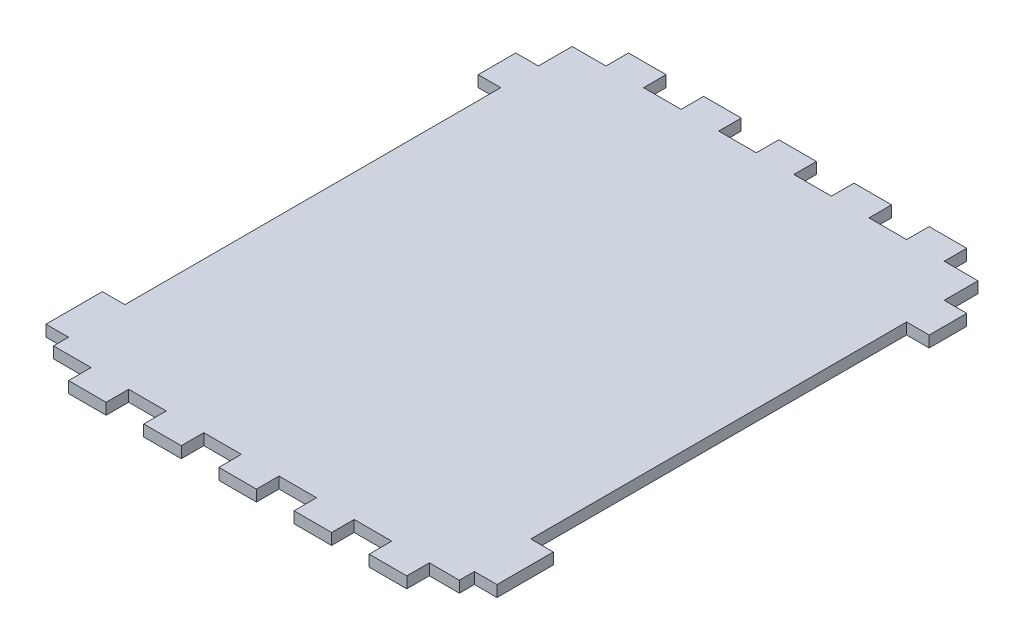
SolidWorks part; units mm, degrees
ref_plane "Спереди" through (0, 0, 0) normal (0, 0, 1) x (1, 0, 0)
ref_plane "Сверху" through (0, 0, 0) normal (0, 1, 0) x (1, 0, 0)
ref_plane "Справа" through (0, 0, 0) normal (1, 0, 0) x (0, 0, -1)
other "Configuration Table"
sketch "Эскиз1" plane through (0, 0, 0) normal (0, 1, 0) x (1, 0, 0)
  line L1 (0, 0) -> (108, 0)
  line L2 (0, 0) -> (0, -138)
  line L3 (0, -138) -> (108, -138)
  line L4 (108, 0) -> (108, -138)
  dimension "D1" = 138
  dimension "D2" = 108
extrude "Бобышка-Вытянуть1" add sketch "Эскиз1" along normal blind 4
sketch "Эскиз3" plane through (0, 0, 0) normal (0, -1, 0) x (1, 0, 0)
  line L1 (0, 138) -> (108, 138)
  line L2 (0, 138) -> (0, 0)
  line L3 (0, 0) -> (108, 0)
  line L4 (108, 138) -> (108, 0)
extrude "Вырез-Вытянуть2" cut sketch "Эскиз3" against normal blind 1
sketch "Эскиз4" plane through (0, 0, 138) normal (0, 0, 1) x (1, 0, 0)
  line L0 (0, 4) -> (108, 4) construction
  line L1 (10, 4) -> (20, 4)
  line L2 (10, 4) -> (10, 1)
  line L3 (10, 1) -> (20, 1)
  line L4 (20, 4) -> (20, 1)
  line L5 (108, 1) -> (0, 1) construction
  line L6 (0, 4) -> (0, 1) construction
  line L7 (30, 4) -> (30, 1)
  line L8 (30, 4) -> (40, 4)
  line L9 (40, 4) -> (40, 1)
  line L10 (30, 1) -> (40, 1)
  line L11 (50, 4) -> (50, 1)
  line L12 (50, 4) -> (60, 4)
  line L13 (60, 4) -> (60, 1)
  line L14 (50, 1) -> (60, 1)
  line L15 (70, 4) -> (70, 1)
  line L16 (70, 4) -> (80, 4)
  line L17 (80, 4) -> (80, 1)
  line L18 (70, 1) -> (80, 1)
  line L19 (90, 4) -> (90, 1)
  line L20 (90, 4) -> (100, 4)
  line L21 (100, 4) -> (100, 1)
  line L22 (90, 1) -> (100, 1)
  dimension "D1" = 10
  dimension "D2" = 10
  dimension "D3" = 5
extrude "Бобышка-Вытянуть2" add sketch "Эскиз4" along normal blind 6
sketch "Эскиз5" plane through (0, 0, 0) normal (-1, 0, 0) x (0, 0, 1)
  line L0 (0, 4) -> (138, 4) construction
  line L1 (9, 4) -> (19, 4)
  line L2 (9, 4) -> (9, 1)
  line L3 (9, 1) -> (19, 1)
  line L4 (19, 4) -> (19, 1)
  line L5 (138, 1) -> (0, 1) construction
  line L6 (0, 4) -> (0, 1) construction
  line L7 (119, 4) -> (134, 4)
  line L8 (119, 4) -> (119, 1)
  line L9 (119, 1) -> (134, 1)
  line L10 (134, 4) -> (134, 1)
  line L11 (138, 4) -> (138, 1) construction
  dimension "D1" = 10
  dimension "D2" = 9
  dimension "D3" = 15
  dimension "D4" = 4
extrude "Бобышка-Вытянуть3" add sketch "Эскиз5" along normal blind 6
sketch "Эскиз6" plane through (108, 0, 0) normal (1, 0, 0) x (0, 0, -1)
  line L0 (-138, 4) -> (0, 4) construction
  line L1 (-134, 4) -> (-119, 4)
  line L2 (-134, 4) -> (-134, 1)
  line L3 (-134, 1) -> (-119, 1)
  line L4 (-119, 4) -> (-119, 1)
  line L5 (0, 1) -> (-138, 1) construction
  line L6 (-138, 4) -> (-138, 1) construction
  line L7 (-19, 4) -> (-9, 4)
  line L8 (-19, 4) -> (-19, 1)
  line L9 (-19, 1) -> (-9, 1)
  line L10 (-9, 4) -> (-9, 1)
  line L11 (0, 4) -> (0, 1) construction
  dimension "D1" = 15
  dimension "D2" = 4
  dimension "D3" = 10
  dimension "D4" = 9
extrude "Бобышка-Вытянуть4" add sketch "Эскиз6" along normal blind 6
sketch "Эскиз7" plane through (0, 0, 0) normal (0, 0, -1) x (-1, 0, 0)
  line L0 (-108, 4) -> (0, 4) construction
  line L1 (-99, 4) -> (-89, 4)
  line L2 (-99, 4) -> (-99, 1)
  line L3 (-99, 1) -> (-89, 1)
  line L4 (-89, 4) -> (-89, 1)
  line L5 (0, 1) -> (-108, 1) construction
  line L6 (-79, 4) -> (-79, 1)
  line L7 (-79, 4) -> (-69, 4)
  line L8 (-69, 4) -> (-69, 1)
  line L9 (-79, 1) -> (-69, 1)
  line L10 (-59, 4) -> (-59, 1)
  line L11 (-59, 4) -> (-49, 4)
  line L12 (-49, 4) -> (-49, 1)
  line L13 (-59, 1) -> (-49, 1)
  line L14 (-39, 4) -> (-39, 1)
  line L15 (-39, 4) -> (-29, 4)
  line L16 (-29, 4) -> (-29, 1)
  line L17 (-39, 1) -> (-29, 1)
  line L18 (-19, 4) -> (-19, 1)
  line L19 (-19, 4) -> (-9, 4)
  line L20 (-9, 4) -> (-9, 1)
  line L21 (-19, 1) -> (-9, 1)
  line L22 (-108, 4) -> (-108, 1) construction
  dimension "D1" = 10
  dimension "D3" = 9
  dimension "D2" = 5
extrude "Бобышка-Вытянуть5" add sketch "Эскиз7" along normal blind 6
